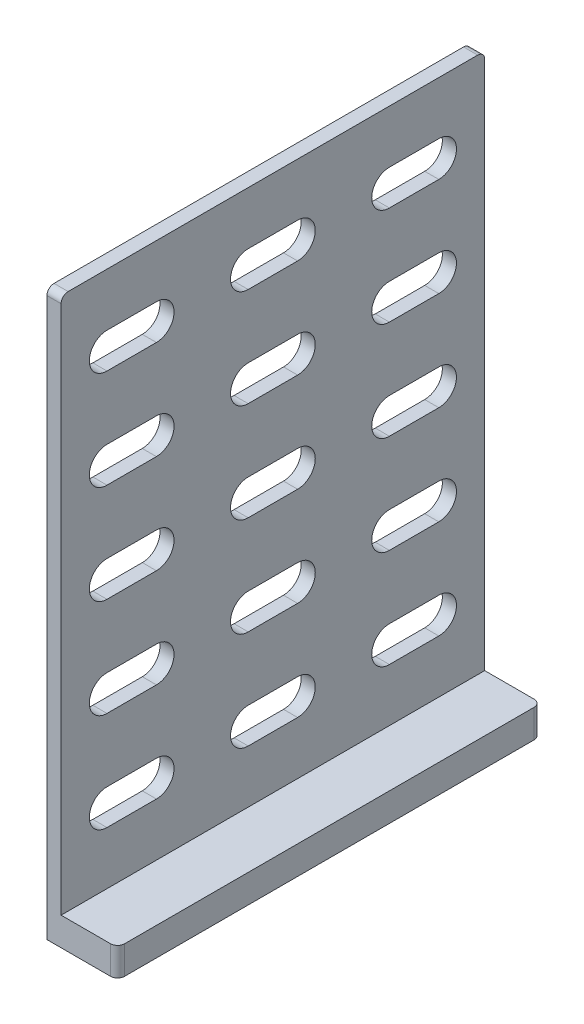
SolidWorks part; units mm, degrees
ref_plane "Přední rovina" through (0, 0, 0) normal (0, 0, 1) x (1, 0, 0)
ref_plane "Horní rovina" through (0, 0, 0) normal (0, 1, 0) x (1, 0, 0)
ref_plane "Pravá rovina" through (0, 0, 0) normal (1, 0, 0) x (0, 0, -1)
sketch "Skica1" plane through (0, 0, 0) normal (0, 0, 1) x (1, 0, 0)
  line L0 (10, 0) -> (0, 0)
  line L1 (0, 0) -> (0, 80)
  line L2 (0, 80) -> (2, 80)
  line L3 (2, 80) -> (2, 4)
  line L4 (2, 4) -> (10, 4)
  line L5 (10, 4) -> (10, 0)
  point P3 (0, 0)
  dimension "D1" = 2
  dimension "D2" = 80
  dimension "D3" = 10
  dimension "D4" = 4
extrude "Přidat vysunutím1" add sketch "Skica1" along normal mid plane 60
sketch "Skica2" plane through (2, 0, 0) normal (1, 0, 0) x (0, 0, -1)
  line L0 (-23.5, 14) -> (-16.5, 14) construction
  line L1 (-23.5, 16.5) -> (-16.5, 16.5)
  line L2 (-23.5, 11.5) -> (-16.5, 11.5)
  line L3 (-30, 4) -> (30, 4) construction
  line L5 (-30, 4) -> (-30, 80) construction
  arc A0 (-23.5, 16.5) -> (-23.5, 11.5) centre (-23.5, 14) ccw
  arc A1 (-16.5, 11.5) -> (-16.5, 16.5) centre (-16.5, 14) ccw
  point P2 (-20, 14)
  point P11 (-26, 14)
  point P12 (-14, 14)
  dimension "D1" = 5
  dimension "D2" = 12
  dimension "D3" = 10
  dimension "D4" = 10
extrude "Odebrat vysunutím1" cut sketch "Skica2" against normal through all contours L1 A1 L2 A0
pattern_linear "LinPole1" count 3 spacing 20 along (0, 0, -1) count 6 spacing 14 along (0, 1, 0) of "Odebrat vysunutím1"
fillet "Zaoblit1" radius 1 4 edges at (10, 2, -30) (10, 2, 30) (1, 80, -30) (1, 80, 30)
